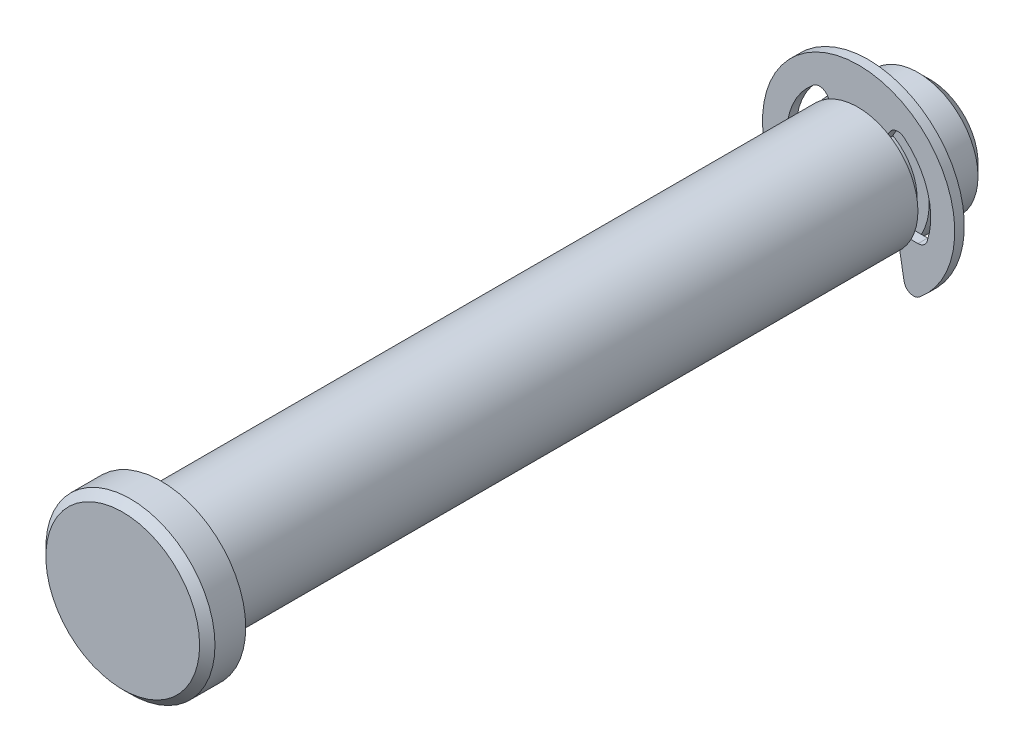
SolidWorks part; units mm, degrees
ref_plane "Front" through (0, 0, 0) normal (0, 0, 1) x (1, 0, 0)
ref_plane "Top" through (0, 0, 0) normal (0, 1, 0) x (1, 0, 0)
ref_plane "Right" through (0, 0, 0) normal (1, 0, 0) x (0, 0, -1)
sketch "Sketch2" plane through (0, 0, 0) normal (0, 0, 1) x (1, 0, 0)
  circle A0 centre (0, 0) radius 3.9688
  point P3 (0, 3.9688)
  point P4 (0, -3.9688)
  dimension "dia" = 7.9375
extrude "Extrude1" add sketch "Sketch2" along normal mid plane 50.8
sketch "Sketch3" plane through (0, 0, 0) normal (1, 0, 0) x (0, 0, -1)
  line L0 (25.4, 3.9688) -> (-25.4, 3.9688) construction
  line L1 (20.6375, 3.9688) -> (21.3741, 3.9688)
  line L2 (20.6375, 3.9688) -> (20.6375, 3.175)
  line L3 (20.6375, 3.175) -> (21.3741, 3.175)
  line L4 (21.3741, 3.9688) -> (21.3741, 3.175)
  line L5 (-25.4, 3.9688) -> (-25.4, -3.9688) construction
  line L10 (21.3741, 3.175) -> (21.3741, -3.175) construction
  point P11 (21.3741, 0)
  point P14 (21.0058, 3.9688)
  dimension "groove wd" = 0.7366
  dimension "groove dia" = 6.35
  dimension "usable lg" = 46.0375
revolve "Cut-Revolve1" cut sketch "Sketch3" angle 360 about axis through (0, 0, 25.4) along (0, 0, -1)
sketch "Sketch8" plane through (0, 0, 25.4) normal (0, 0, 1) x (1, 0, 0)
  circle A0 centre (0, 0) radius 5.588
  dimension "head dia" = 11.176
extrude "Extrude6" add sketch "Sketch8" along normal blind 2.54
chamfer "Chamfer2" distance 0.508 angle 45 1 edges at (5.588, 0, 27.94)
ref_plane "Plane1" through (0, 0, -21.0058) normal (0, 0, 1) x (1, 0, 0)
sketch "Sketch4" plane through (0, 0, -21.0058) normal (0, 0, 1) x (1, 0, 0)
  line L0 (0, 3.175) -> (0, -3.175) construction
  circle A0 centre (0, 0) radius 6.35
  circle A1 centre (0, 0) radius 3.175
  dimension "ring dia" = 12.7
extrude "Extrude2" add sketch "Sketch4" along normal mid plane 0.635 separate body
sketch "Sketch5" plane through (0, 0, 0) normal (0, 0, 1) x (1, 0, 0)
  line L0 (0, 6.35) -> (0, 3.175) construction
  line L1 (-2.3813, 4.1244) -> (0, 0)
  line L2 (-4.3649, -1.905) -> (-2.54, -1.905)
  line L3 (0, 0) -> (2.3813, 4.1244)
  line L4 (-2.54, -1.905) -> (-3.1739, -5.4999)
  line L5 (2.54, -1.905) -> (3.1739, -5.4999)
  line L6 (2.54, -1.905) -> (4.3649, -1.905)
  arc A0 (-2.3813, 4.1244) -> (-4.3649, -1.905) centre (0, 0) ccw
  circle A1 centre (0, 0) radius 6.35 construction
  circle A2 centre (0, 0) radius 3.175 construction
  arc A3 (4.3649, -1.905) -> (2.3813, 4.1244) centre (0, 0) ccw
  arc A4 (-3.1739, -5.4999) -> (3.1739, -5.4999) centre (0, 0) ccw
  circle A5 centre (0, 0) radius 3.175 construction
  point P10 (0, 4.7625)
  dimension "D1" = 30
  dimension "D2" = 10
  dimension "D3" = 1.905
extrude "Extrude4" cut sketch "Sketch5" against normal through all
sketch "Sketch6" plane through (0, 0, -20.6883) normal (0, 0, 1) x (1, 0, 0)
  line L0 (-1.5875, 2.7496) -> (1.5875, 2.7496)
  circle A0 centre (0, 0) radius 3.175 construction
  arc A1 (1.5875, 2.7496) -> (-1.5875, 2.7496) centre (0, 0) ccw
extrude "Extrude5" add sketch "Sketch6" against normal up to surface (0.635 mm away) up to face at (0, 0.8161, -21.3233)
fillet "Fillet1" radius 0.635 6 edges at (3.1739, -5.4999, -21.0058) (-3.1739, -5.4999, -21.0058) (4.3649, -1.905, -21.0058) (2.3813, 4.1244, -21.0058) (-2.3813, 4.1244, -21.0058) (-4.3649, -1.905, -21.0058)
chamfer "Chamfer1" distance 0.7937 angle 45 1 edges at (3.9688, 0, -25.4)
sketch "Sketch7" plane through (0, 0, 0) normal (1, 0, 0) x (0, 0, -1)
  line L0 (21.3233, 6.35) -> (20.6883, 6.35) construction
  line L1 (25.4, -3.9688) -> (25.4, 3.9688) construction
  line L2 (20.6883, -5.0511) -> (21.3233, -5.0511) construction
  line L3 (-27.94, 5.08) -> (-27.94, -5.08) construction
  point P0 (21.3741, -5.0511)
  point P1 (25.4, 3.9688)
  point P2 (-27.94, 5.588)
  point P6 (20.6375, 6.35)
  point P7 (25.4, -3.9688)
  point P12 (-25.4, 5.588)
  point P16 (20.6375, -5.0511)
equation "\"D1@Chamfer1\" = \"dia@Sketch2\" * .1"
equation "\"D1@Fillet1\" = \"ring dia@Sketch4\" * .05"
equation "\"D3@Sketch5\" = \"groove dia@Sketch3\" * .3"
equation "\"D1@Chamfer2\" = \"head ht@Extrude6\" * .2"
